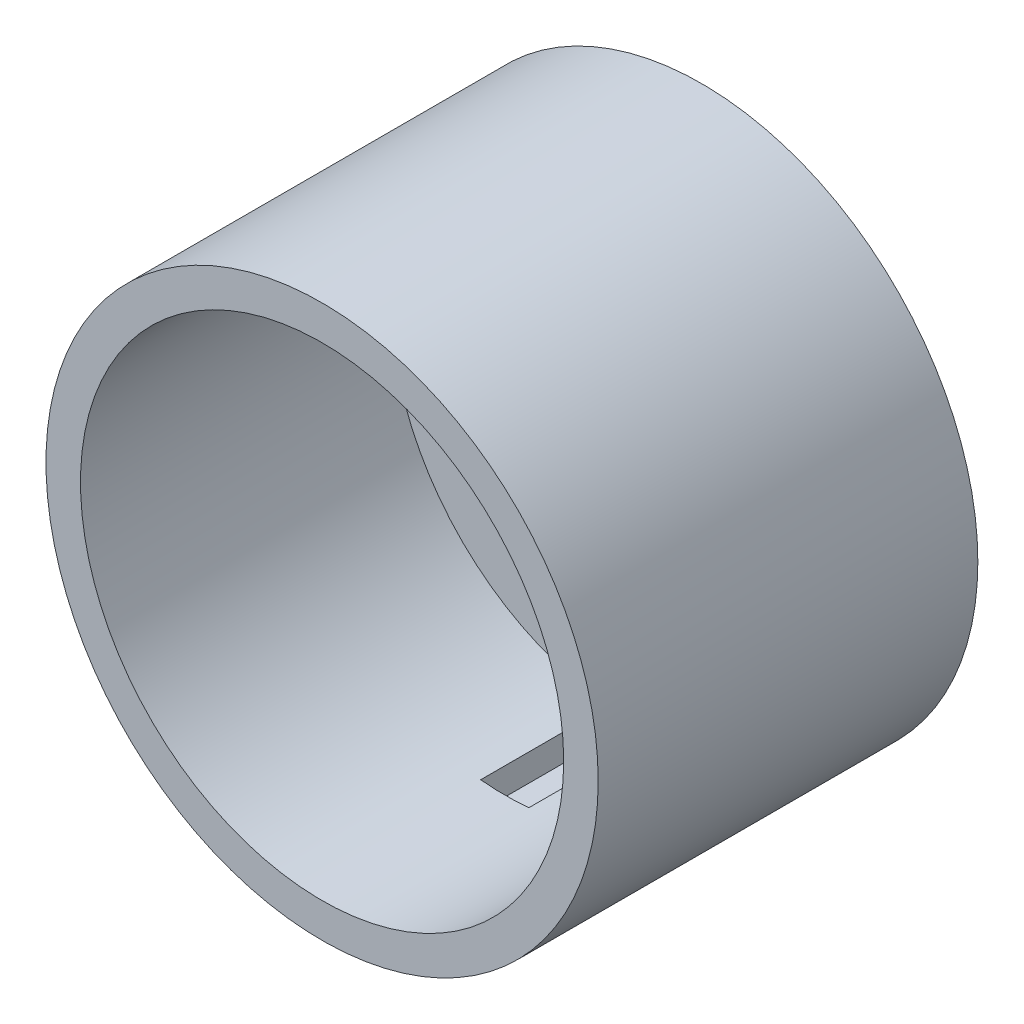
SolidWorks part; units mm, degrees
ref_plane "Plan de face" through (0, 0, 0) normal (0, 0, 1) x (1, 0, 0)
ref_plane "Plan de dessus" through (0, 0, 0) normal (0, 1, 0) x (1, 0, 0)
ref_plane "Plan de droite" through (0, 0, 0) normal (1, 0, 0) x (0, 0, -1)
sketch "Esquisse1" plane through (0, 0, 0) normal (0, 0, 1) x (1, 0, 0)
  circle A0 centre (0, 0) radius 16
extrude "Boss.-Extru.1" add sketch "Esquisse1" along normal blind 22
sketch "Esquisse2" plane through (0, 0, 0) normal (0, 0, 1) x (1, 0, 0)
  line L1 (-1.4, 15.5) -> (1.4, 15.5)
  line L2 (-1.4, 15.5) -> (-1.4, -15.5)
  line L3 (-1.4, -15.5) -> (1.4, -15.5)
  line L4 (1.4, 15.5) -> (1.4, -15.5)
  dimension "D1" = 31
  dimension "D2" = 2.8
  dimension "D3" = 1.4
  dimension "D4" = 15.5
extrude "Enlèv. mat.-Extru.1" cut sketch "Esquisse2" along normal blind 11.41
sketch "Esquisse3" plane through (0, 0, 0) normal (0, 0, -1) x (-1, 0, 0)
  line L0 (-1.4, -15.5) -> (-1.4, 15.5) construction
  line L5 (1.4, 15.5) -> (1.4, -15.5) construction
  line L7 (-1.4, 15.5) -> (1.4, 15.5) construction
  line L8 (-1.4, 5) -> (1.4, 5)
  line L9 (-1.4, 5) -> (-1.4, 3.3)
  line L10 (-1.4, 3.3) -> (1.4, 3.3)
  line L11 (1.4, 5) -> (1.4, 3.3)
  dimension "D3" = 1.7
  dimension "D4" = 10.5
extrude "Boss.-Extru.2" add sketch "Esquisse3" against normal blind 5
sketch "Esquisse4" plane through (0, 0, 22) normal (0, 0, 1) x (1, 0, 0)
  circle A0 centre (0, 0) radius 14
extrude "Enlèv. mat.-Extru.2" cut sketch "Esquisse4" against normal blind 18
